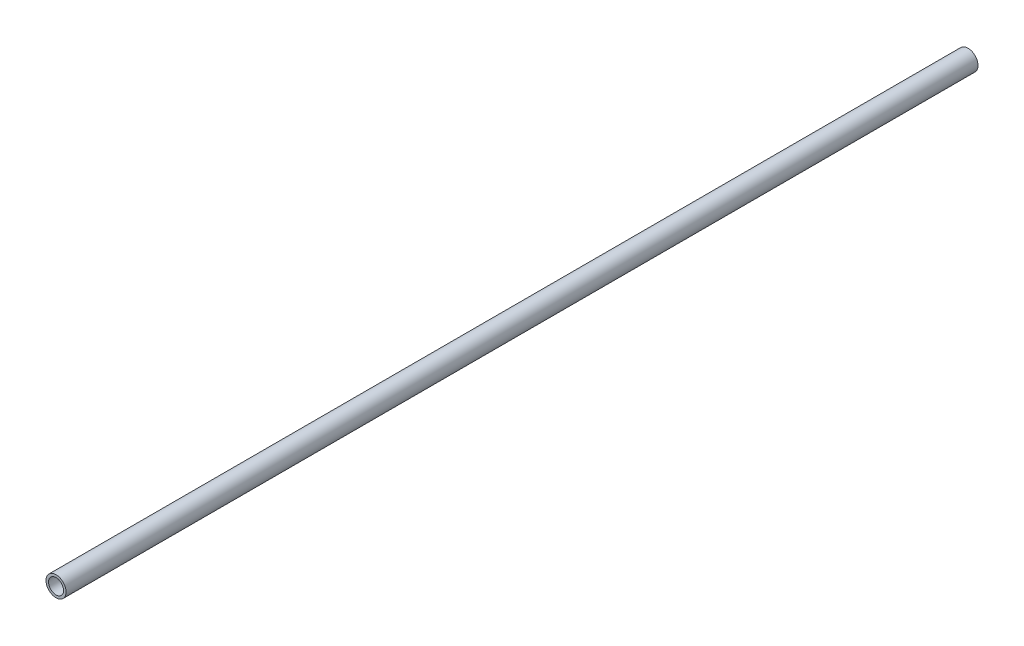
SolidWorks part; units mm, degrees
ref_plane "Front Plane" through (0, 0, 0) normal (0, 0, 1) x (1, 0, 0)
ref_plane "Top Plane" through (0, 0, 0) normal (0, 1, 0) x (1, 0, 0)
ref_plane "Right Plane" through (0, 0, 0) normal (1, 0, 0) x (0, 0, -1)
sketch "Sketch1" plane through (0, 0, 0) normal (0, 0, 1) x (1, 0, 0)
  circle A0 centre (0, 0) radius 9.525
  circle A1 centre (0, 0) radius 7.1438
  dimension "D1" = 19.05
  dimension "D2" = 14.2875
extrude "Boss-Extrude1" add sketch "Sketch1" along normal blind 865.378
equation "\"span\"= 48"
equation "\"wing_chord\"= 9"
equation "\"fuse_len\"= 15"
equation "\"fuse_height\"= 5"
equation "\"fuse_wid\"= 5"
equation "\"foam_t\"= 0.1875"
equation "\"main_spar_len\"= 36"
equation "\"D1@Boss-Extrude1\"=\"main_spar_stickout\" + \"x_fuse_to_wing\" + \"tail_arm\" + \"tail_mount_l\""
equation "\"x_fuse_to_wing\"= 3"
equation "\"x_cg_from_le\"= 2.25"
equation "\"boom_len\"= 30"
equation "\"wing_angle\"= 1.5"
equation "\"boom_d\"= 0.75"
equation "\"wing_spar_d\"= 0.375"
equation "\"wing_spar_l\"= 48"
equation "\"wing_spar_spacing\"= 1.35"
equation "\"wing_mount_l\"= 2.5"
equation "\"boom_mount_l\"= 1"
equation "\"vstab_span\"= 6.5"
equation "\"hstab_span\"= 15.25"
equation "\"tail_chord\"= 5"
equation "\"wing_spar_ID\"= 0.25"
equation "\"fuse_inner_arc_length\"= 0.5"
equation "\"fuse_inner_r\"= \"fuse_inner_arc_length\" * 4 / (2*pi)"
equation "\"fuse_outer_r\"= \"fuse_inner_r\" + \"foam_t\""
equation "\"wing_mount_bolt_spacing\"= \"wing_mount_l\" * 0.5"
equation "\"fuse_inner_h\"= \"fuse_height\" - 2 * \"foam_t\""
equation "\"fuse_inner_w\"= \"fuse_wid\" - 2 * \"fuse_outer_r\""
equation "\"wing_mount_y\"= 36"
equation "\"tail_mount_l\"= 4.67"
equation "\"tail_arm\"= 25.5"
equation "\"main_spar_stickout\"= 0.9"
